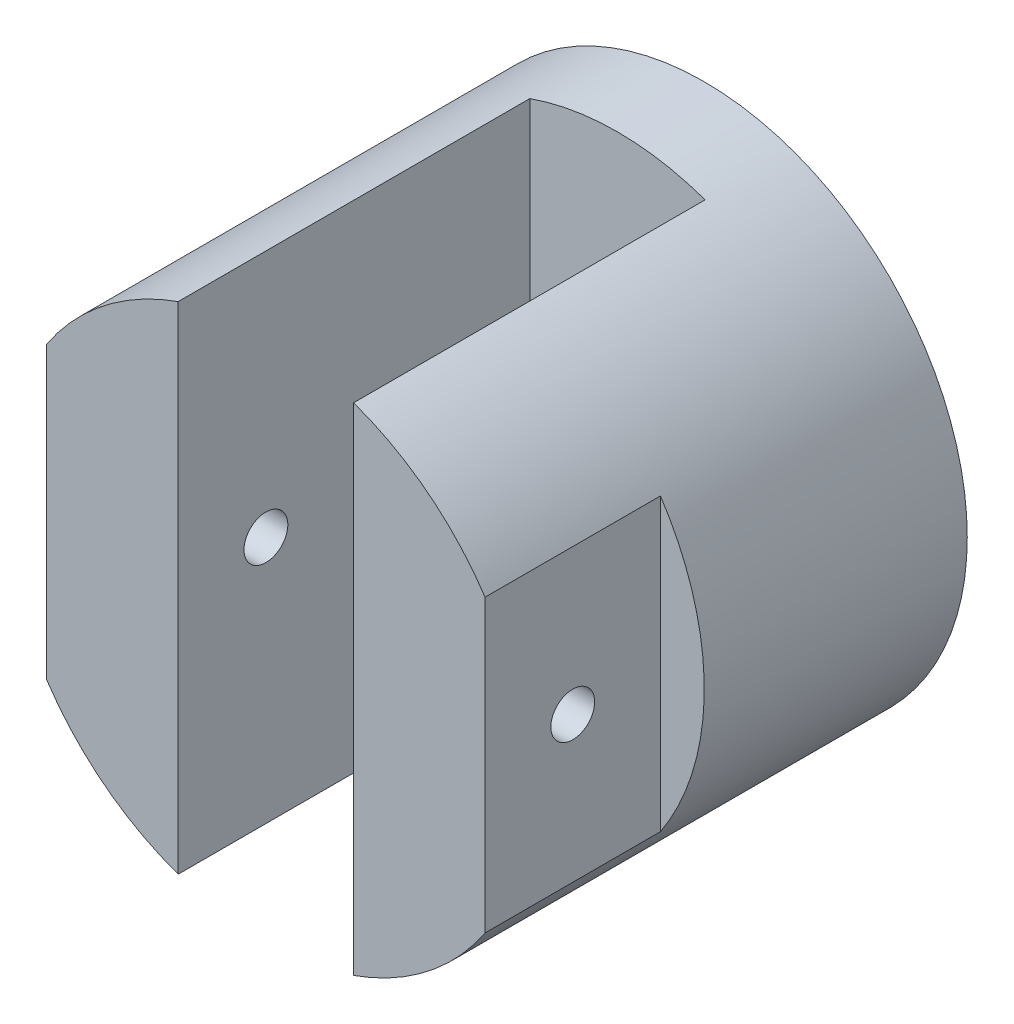
SolidWorks part; units mm, degrees
material "6061 Alloy"
ref_plane "Front Plane" through (0, 0, 0) normal (0, 0, 1) x (1, 0, 0)
ref_plane "Top Plane" through (0, 0, 0) normal (0, 1, 0) x (1, 0, 0)
ref_plane "Right Plane" through (0, 0, 0) normal (1, 0, 0) x (0, 0, -1)
sketch "Sketch1" plane through (0, 0, 0) normal (0, 0, 1) x (1, 0, 0)
  circle A0 centre (0, 0) radius 38.1
  dimension "D1" = 76.2
extrude "OD Don't Care" add sketch "Sketch1" along normal blind 63.5
sketch "Sketch2" plane through (0, 0, 0) normal (1, 0, 0) x (0, 0, -1)
  line L0 (-63.5, 38.1) -> (-63.5, -38.1) construction
  circle A0 centre (-50.8, 0) radius 3.175
  dimension "D1" = 6.35
  dimension "D2" = 12.7
extrude "2x 1/4\" Through Hole" cut sketch "Sketch2" against normal mid plane 101.6
sketch "Sketch3" plane through (0, 0, 0) normal (0, 1, 0) x (1, 0, 0)
  line L0 (-38.1, -63.5) -> (38.1, -63.5) construction
  line L1 (-12.7, -12.573) -> (12.7, -12.573)
  line L2 (-12.7, -12.573) -> (-12.7, -63.5)
  line L3 (-12.7, -63.5) -> (12.7, -63.5)
  line L4 (12.7, -12.573) -> (12.7, -63.5)
  line L5 (-12.7, -12.573) -> (12.7, -63.5) construction
  line L6 (-12.7, -63.5) -> (12.7, -12.573) construction
  line L7 (38.1, 0) -> (-38.1, 0) construction
  point P0 (0, -38.0365)
  dimension "D1" = 25.4
  dimension "D2" = 12.573
extrude "Slot" cut sketch "Sketch3" against normal mid plane 101.6
sketch "Sketch4" plane through (0, 0, 12.573) normal (0, 0, 1) x (1, 0, 0)
  circle A0 centre (0, 0) radius 7.9375
  dimension "D1" = 15.875
extrude "5/8\" Through Hole" cut sketch "Sketch4" against normal through all
sketch "Sketch5" plane through (0, 0, 63.5) normal (0, 0, 1) x (1, 0, 0)
  line L1 (-31.75, -35.921) -> (31.75, -35.921)
  line L2 (-31.75, -35.921) -> (-31.75, 35.921)
  line L3 (-31.75, 35.921) -> (31.75, 35.921)
  line L4 (31.75, -35.921) -> (31.75, 35.921)
  line L5 (-31.75, -35.921) -> (31.75, 35.921) construction
  line L6 (-31.75, 35.921) -> (31.75, -35.921) construction
  point P0 (0, 0)
  dimension "D1" = 63.5
extrude "Flat Surface for 3/4\" Long Shoulder" cut sketch "Sketch5" against normal blind 25.4 flip side to cut
